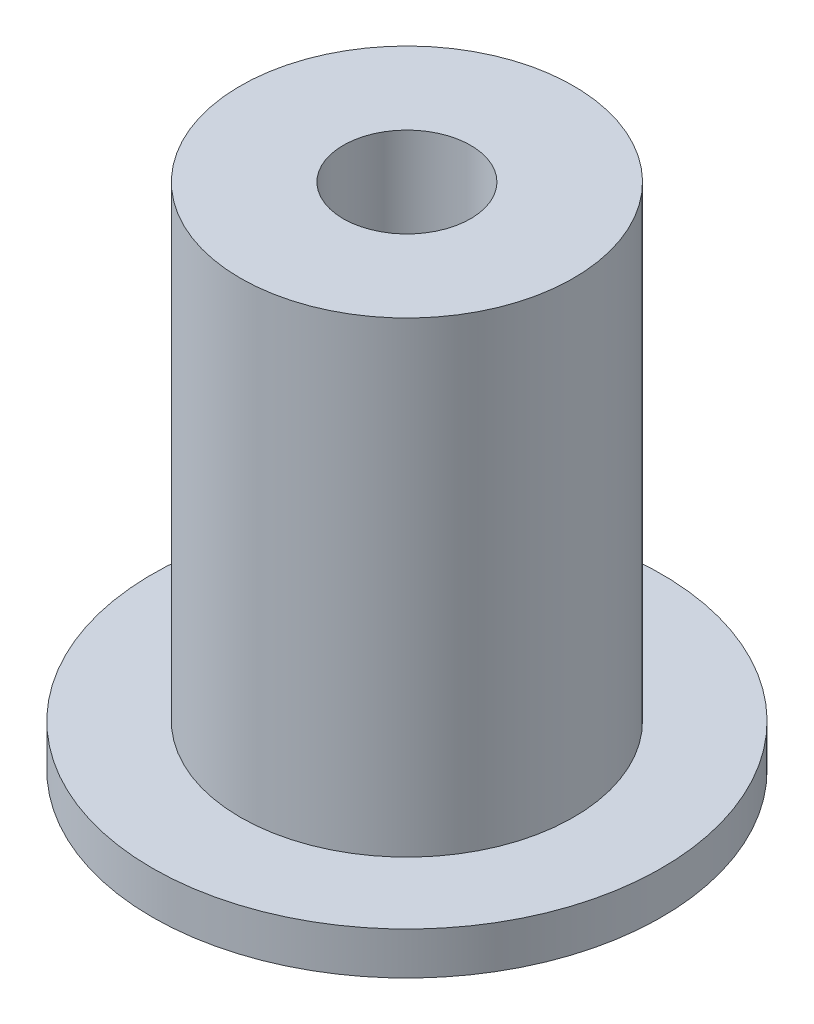
SolidWorks part; units mm, degrees
ref_plane "Ebene vorne" through (0, 0, 0) normal (0, 0, 1) x (1, 0, 0)
ref_plane "Ebene oben" through (0, 0, 0) normal (0, 1, 0) x (1, 0, 0)
ref_plane "Ebene rechts" through (0, 0, 0) normal (1, 0, 0) x (0, 0, -1)
sketch "Skizze1" plane through (0, 0, 0) normal (0, 1, 0) x (1, 0, 0)
  circle A0 centre (0, 0) radius 1.5
  circle A1 centre (0, 0) radius 6
  dimension "D1" = 3
  dimension "D2" = 12
extrude "Aufsatz-Linear austragen1" add sketch "Skizze1" along normal blind 1
sketch "Skizze2" plane through (0, 1, 0) normal (0, 1, 0) x (1, 0, 0)
  circle A0 centre (0, 0) radius 3.925
  circle A1 centre (0, 0) radius 1.5
  dimension "D1" = 7.85
  dimension "D2" = 3
extrude "Aufsatz-Linear austragen2" add sketch "Skizze2" along normal blind 11
